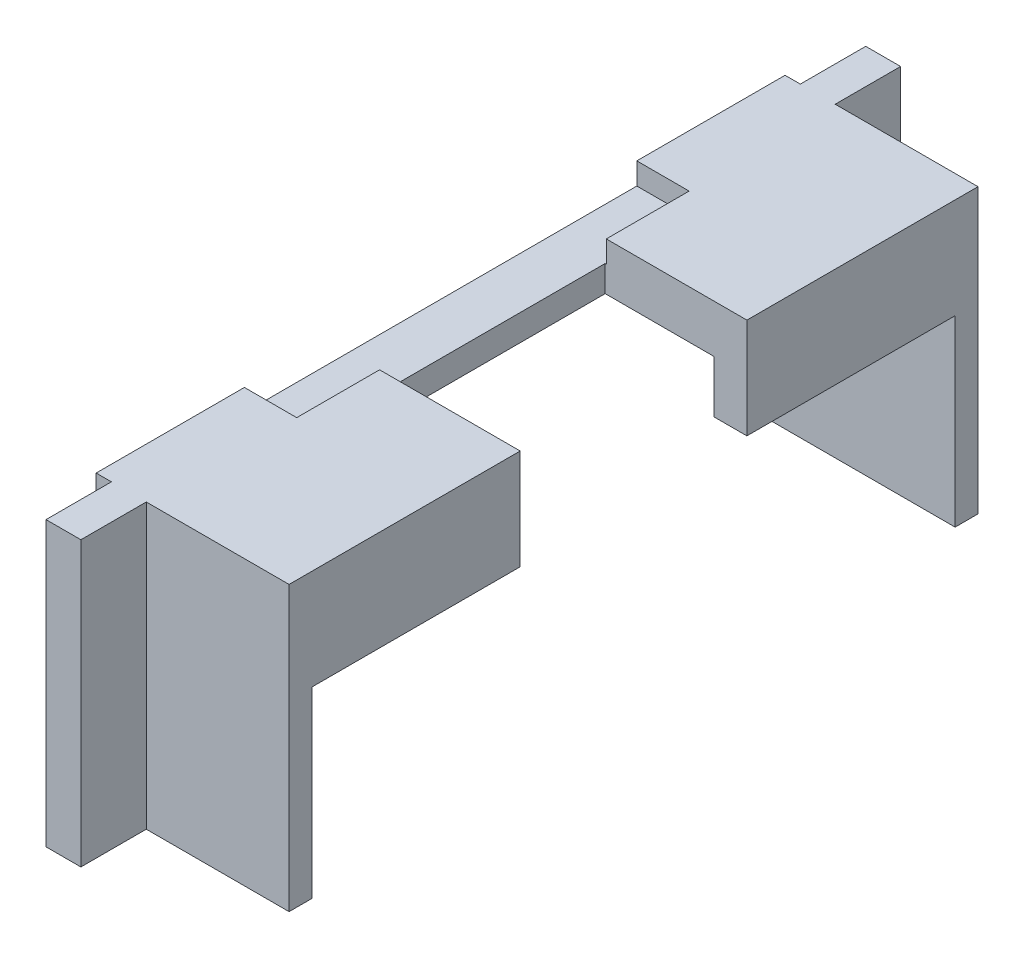
SolidWorks part; units mm, degrees
ref_plane "Front Plane" through (0, 0, 0) normal (0, 0, 1) x (1, 0, 0)
ref_plane "Top Plane" through (0, 0, 0) normal (0, 1, 0) x (1, 0, 0)
ref_plane "Right Plane" through (0, 0, 0) normal (1, 0, 0) x (0, 0, -1)
sketch "Sketch1" plane through (0, 0, 0) normal (1, 0, 0) x (0, 0, -1)
  line L0 (0, 13) -> (0, 0) construction
  line L1 (-19, 13) -> (19, 13)
  line L2 (19, 13) -> (19, 0)
  line L3 (19, 0) -> (-19, 0)
  line L4 (-19, 13) -> (-19, 0)
  dimension "D1" = 13
  dimension "D2" = 38
extrude "Boss-Extrude1" add sketch "Sketch1" along normal blind 3
sketch "Sketch2" plane through (0, 13, 0) normal (0, 1, 0) x (1, 0, 0)
  line L0 (0.7, -18.8) -> (0.7, -15.8)
  line L1 (3, -19) -> (0, -19) construction
  line L2 (0.7, -15.8) -> (0, -15.8)
  line L3 (0, 19) -> (0, -19) construction
  line L4 (1.5, -19) -> (1.5, 19) construction
  line L5 (3, 19) -> (0, 19) construction
  line L6 (0, 0) -> (3, 0) construction
  line L7 (3, 19) -> (3, -19) construction
  line L9 (0, -19) -> (0, -15.8)
  line L22 (0.7, -18.8) -> (2.3, -18.8)
  line L23 (0, -19) -> (3, -19)
  line L24 (3, -19) -> (3, -15.8)
  line L25 (2.3, -15.8) -> (3, -15.8)
  line L26 (2.3, -18.8) -> (2.3, -15.8)
  line L27 (2.3, 18.8) -> (2.3, 15.8)
  line L28 (2.3, 15.8) -> (3, 15.8)
  line L29 (3, 19) -> (3, 15.8)
  line L30 (0, 19) -> (3, 19)
  line L31 (0.7, 18.8) -> (2.3, 18.8)
  line L32 (0, 19) -> (0, 15.8)
  line L33 (0.7, 15.8) -> (0, 15.8)
  line L34 (0.7, 18.8) -> (0.7, 15.8)
  point P18 (1.5, -18.8)
  point P30 (1.5, 18.8)
  dimension "D1" = 1.6
  dimension "D2" = 3.2
  dimension "D3" = 0.2
extrude "Cut-Extrude1" cut sketch "Sketch2" against normal through all
sketch "Sketch3" plane through (3, 0, 0) normal (1, 0, 0) x (0, 0, -1)
  line L0 (-14.75, 0) -> (-14.75, 10.8)
  line L1 (-15.8, 0) -> (15.8, 0) construction
  line L2 (-14.75, 10.8) -> (14.75, 10.8)
  line L3 (0, 10.8) -> (0, 0) construction
  line L4 (15.8, 13) -> (-15.8, 13) construction
  line L6 (14.75, 0) -> (14.75, 10.8)
  line L7 (-14.75, 0) -> (14.75, 0)
  dimension "D1" = 2.2
  dimension "D2" = 29.5
extrude "Cut-Extrude2" cut sketch "Sketch3" against normal blind 3
sketch "Sketch4" plane through (3, 0, 0) normal (1, 0, 0) x (0, 0, -1)
  line L0 (-15.8, 13) -> (-15.8, 0)
  line L1 (-15.8, 0) -> (-14.75, 0)
  line L2 (-14.75, 0) -> (-14.75, 10.8)
  line L3 (-14.75, 10.8) -> (14.75, 10.8)
  line L4 (14.75, 10.8) -> (-14.75, 10.8) construction
  line L5 (14.75, 10.8) -> (14.75, 0)
  line L6 (14.75, 0) -> (15.8, 0)
  line L7 (15.8, 0) -> (15.8, 13)
  line L8 (15.8, 13) -> (-15.8, 13)
extrude "Boss-Extrude2" add sketch "Sketch4" along normal blind 5.85
sketch "Sketch5" plane through (8.85, 0, 0) normal (1, 0, 0) x (0, 0, -1)
  line L2 (-5, 10.8) -> (-5, 8.4)
  line L5 (-5, 16) -> (-5, 2) construction
  line L6 (-14.75, 10.8) -> (14.75, 10.8) construction
  line L7 (-5, 10.8) -> (-14.75, 10.8)
  line L8 (14.75, 8.4) -> (-14.75, 8.4) construction
  line L9 (-5, 8.4) -> (-14.75, 8.4)
  line L10 (-14.75, 0) -> (-14.75, 10.8) construction
  line L11 (-14.75, 8.4) -> (-14.75, 10.8)
  line L12 (0, 0) -> (0, 10.7) construction
  line L13 (-14.75, 0) -> (14.75, 0) construction
  line L14 (3.9375, 10.7) -> (-3.9375, 10.7) construction
  line L15 (14.75, 8.4) -> (14.75, 10.8)
  line L16 (5, 8.4) -> (14.75, 8.4)
  line L17 (5, 10.8) -> (14.75, 10.8)
  line L18 (5, 10.8) -> (5, 8.4)
extrude "Boss-Extrude3" add sketch "Sketch5" against normal blind 1.5
sketch "Sketch6" plane through (0, 13, 0) normal (0, 1, 0) x (1, 0, 0)
  line L0 (0, 0) -> (8.85, 0) construction
  line L1 (8.85, 15.8) -> (8.85, -15.8) construction
  line L3 (8.85, 5.2) -> (2.35, 5.2)
  line L5 (8.85, 5.2) -> (8.85, -5.2)
  line L6 (2.35, 5.2) -> (2.35, 0)
  line L7 (2.35, 0) -> (2.35, -5.2)
  line L8 (2.35, -5.2) -> (8.85, -5.2)
  dimension "D1" = 10.4
  dimension "D2" = 5.2
  dimension "D3" = 6.5
extrude "Cut-Extrude3" cut sketch "Sketch6" against normal blind 10
sketch "Sketch7" plane through (0, 0, 0) normal (-1, 0, 0) x (0, 0, 1)
  line L0 (0, 13) -> (0, 0) construction
  line L1 (-15.8, 13) -> (15.8, 13) construction
  line L2 (-9, 13) -> (9, 13)
  line L3 (9, 13) -> (9, 12)
  line L4 (9, 12) -> (-9, 12)
  line L5 (-9, 13) -> (-9, 12)
  point P9 (0, 12)
  dimension "D1" = 18
  dimension "D2" = 1
extrude "Cut-Extrude4" cut sketch "Sketch7" against normal blind 2.4
